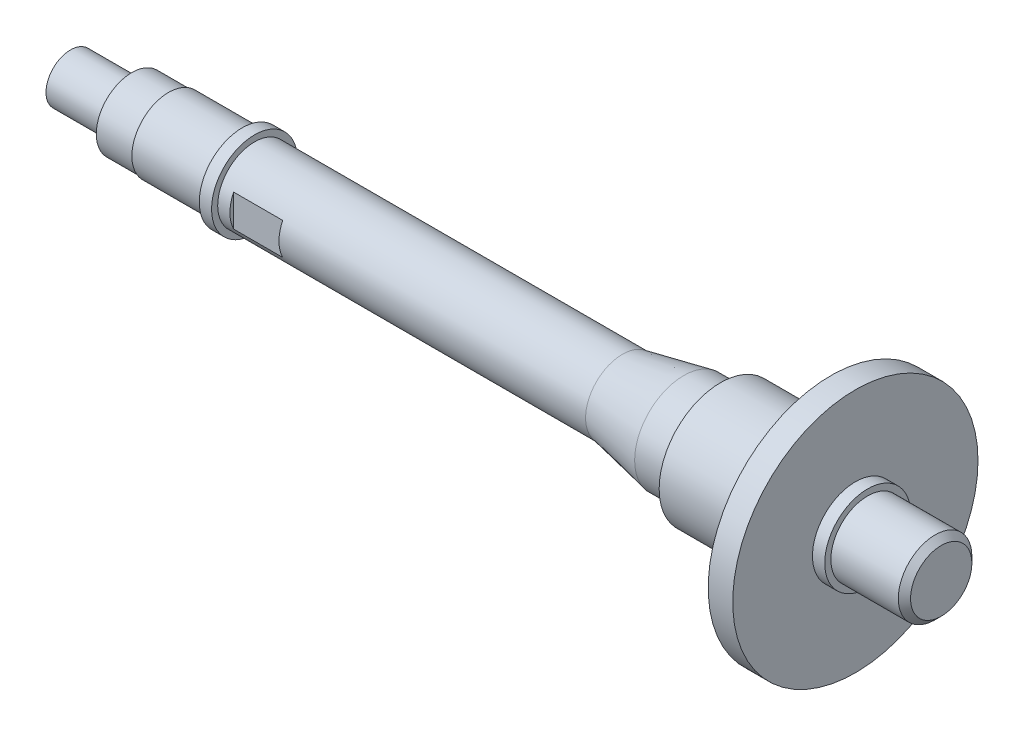
SolidWorks part; units mm, degrees
ref_plane "前视基准面" through (0, 0, 0) normal (0, 0, 1) x (1, 0, 0)
ref_plane "上视基准面" through (0, 0, 0) normal (0, 1, 0) x (1, 0, 0)
ref_plane "右视基准面" through (0, 0, 0) normal (1, 0, 0) x (0, 0, -1)
sketch "草图1" plane through (0, 0, 0) normal (1, 0, 0) x (0, 0, -1)
  circle A0 centre (0, 0) radius 10
  dimension "D1" = 20
extrude "凸台-拉伸1" add sketch "草图1" along normal blind 2
sketch "草图2" plane through (2, 0, 0) normal (1, 0, 0) x (0, 0, -1)
  circle A0 centre (0, 0) radius 3.5
  dimension "D1" = 7
extrude "凸台-拉伸2" add sketch "草图2" along normal blind 1
sketch "草图3" plane through (0, 0, 0) normal (-1, 0, 0) x (0, 0, 1)
  circle A0 centre (0, 0) radius 6
  dimension "D1" = 12
extrude "凸台-拉伸3" add sketch "草图3" along normal blind 9
sketch "草图4" plane through (-9, 0, 0) normal (-1, 0, 0) x (0, 0, 1)
  circle A0 centre (0, 0) radius 4
  dimension "D1" = 8
extrude "凸台-拉伸4" add sketch "草图4" along normal blind 3
sketch "草图5" plane through (3, 0, 0) normal (1, 0, 0) x (0, 0, -1)
  circle A0 centre (0, 0) radius 3
  dimension "D1" = 6
extrude "凸台-拉伸5" add sketch "草图5" along normal blind 6
sketch "草图6" plane through (-12, 0, 0) normal (-1, 0, 0) x (0, 0, 1)
  circle A0 centre (0, 0) radius 3
  dimension "D1" = 6
extrude "凸台-拉伸6" add sketch "草图6" along normal blind 35
sketch "草图7" plane through (-47, 0, 0) normal (-1, 0, 0) x (0, 0, 1)
  circle A0 centre (0, 0) radius 3.5
  dimension "D1" = 7
extrude "凸台-拉伸7" add sketch "草图7" along normal blind 1
sketch "草图8" plane through (-48, 0, 0) normal (-1, 0, 0) x (0, 0, 1)
  circle A0 centre (0, 0) radius 3
  dimension "D1" = 6
extrude "凸台-拉伸8" add sketch "草图8" along normal blind 9
sketch "草图9" plane through (-57, 0, 0) normal (-1, 0, 0) x (0, 0, 1)
  circle A0 centre (0, 0) radius 2
  dimension "D1" = 4
extrude "凸台-拉伸9" add sketch "草图9" along normal blind 5
cosmetic thread "装饰螺纹线3" parameters "D1"=3, "D2"=3
chamfer "倒角1" distance 0.5 angle 45 1 edges at (9, 0, -3)
sketch "草图11" plane through (0, 0, 0) normal (0, 1, 0) x (1, 0, 0)
  line L0 (-47, 0) -> (-39.7359, 0) construction
  line L1 (-46, 3) -> (-42, 3)
  line L2 (-46, 3) -> (-46, 2.7)
  line L3 (-46, 2.7) -> (-42, 2.7)
  line L4 (-42, 3) -> (-42, 2.7)
  line L5 (-47, -3.5) -> (-47, 3.5) construction
  line L6 (-46, -3) -> (-46, -2.7)
  line L7 (-46, -2.7) -> (-42, -2.7)
  line L8 (-42, -3) -> (-42, -2.7)
  line L9 (-46, -3) -> (-42, -3)
  line L10 (-12, 3) -> (-47, 3) construction
  dimension "D1" = 4
  dimension "D2" = 0.3
  dimension "D3" = 1
  dimension "D4" = 0
extrude "切除-拉伸2" cut sketch "草图11" against normal mid plane 10
sketch "草图12" plane through (0, 0, 0) normal (-1, 0, 0) x (0, 0, 1)
  circle A0 centre (0, 0) radius 4.5
  circle A1 centre (0, 0) radius 6
  dimension "D1" = 12
  dimension "D2" = 9
extrude "切除-拉伸3" cut sketch "草图12" along normal blind 1 from offset 2
sketch "草图13" plane through (-9, 0, 0) normal (-1, 0, 0) x (0, 0, 1)
  circle A0 centre (0, 0) radius 5
  circle A1 centre (0, 0) radius 6
  dimension "D1" = 12
  dimension "D2" = 10
extrude "切除-拉伸4" cut sketch "草图13" against normal blind 6
cosmetic thread "装饰螺纹线4" parameters "D2"=9
sketch "草图14" plane through (0, 0, 0) normal (0, 0, 1) x (1, 0, 0)
  line L0 (-12, 4) -> (-17, 3)
  line L1 (-12, 3) -> (-47, 3) construction
  line L2 (-17, 3) -> (-12, 3)
  line L3 (-12, 3) -> (-12, 4)
  line L4 (-6.2386, 0) -> (-21.5744, 0) construction
  dimension "D1" = 5
revolve "旋转1" add sketch "草图14" angle 360 about L4
sketch "草图15" plane through (-57, 0, 0) normal (-1, 0, 0) x (0, 0, 1)
  circle A0 centre (0, 0) radius 2.9
  circle A1 centre (0, 0) radius 3
  dimension "D1" = 6
  dimension "D2" = 5.8
extrude "切除-拉伸5" cut sketch "草图15" against normal blind 3
